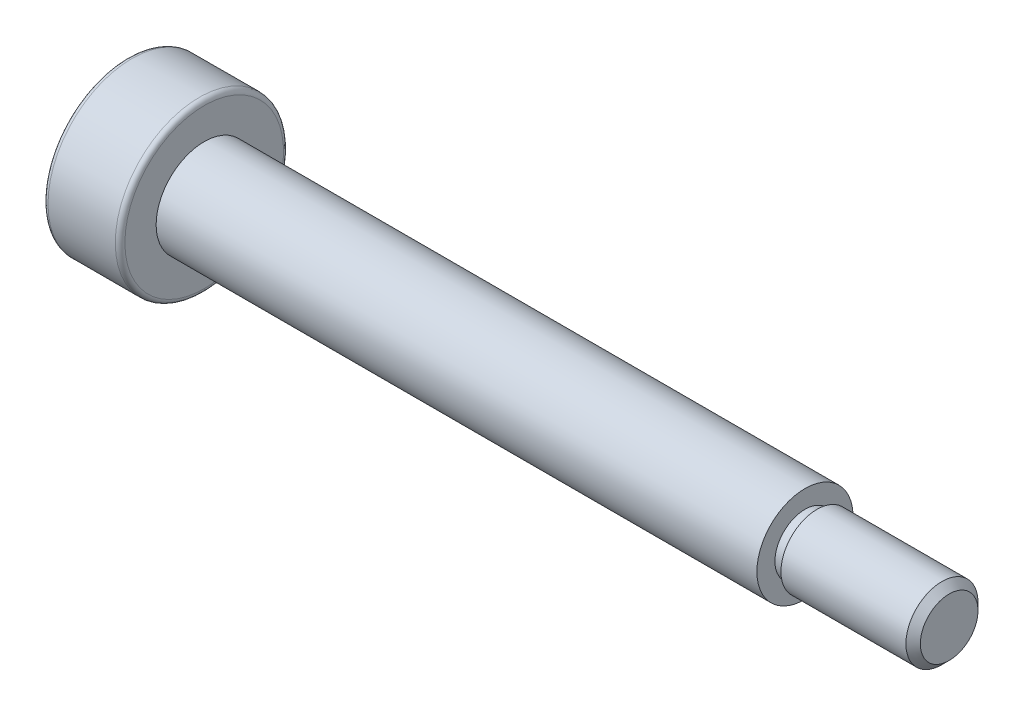
SolidWorks part; units mm, degrees
ref_plane "前视基准面" through (0, 0, 0) normal (0, 0, 1) x (1, 0, 0)
ref_plane "上视基准面" through (0, 0, 0) normal (0, 1, 0) x (1, 0, 0)
ref_plane "右视基准面" through (0, 0, 0) normal (1, 0, 0) x (0, 0, -1)
sketch "草图1" plane through (0, 0, 0) normal (0, 0, 1) x (1, 0, 0)
  line L0 (-17.1, 0) -> (17.1, 0) construction
  line L1 (-17.1, 0) -> (-17.1, 3.5)
  line L2 (-17.1, 3.5) -> (-13.9, 3.5)
  line L3 (-13.9, 3.5) -> (-13.9, 2)
  line L4 (-13.9, 2) -> (11.1, 2)
  line L5 (11.1, 2) -> (11.1, 1.5)
  line L6 (11.1, 1.5) -> (17.1, 1.5)
  line L7 (17.1, 1.5) -> (17.1, 0)
  line L8 (-17.1, 0) -> (17.1, 0)
  dimension "D1" = 4
  dimension "D2" = 7
  dimension "D3" = 3
  dimension "D4" = 6
  dimension "D5" = 25
  dimension "D6" = 3.2
revolve "旋转1" add sketch "草图1" angle 360 about L0
fillet "圆角1" radius 0.2 2 edges at (-13.9, 0, 3.5) (-17.1, 0, 3.5)
chamfer "倒角1" distance 0.3 angle 45 1 edges at (17.1, 0, 1.5)
sketch "草图3" plane through (0, 0, 0) normal (0, 0, 1) x (1, 0, 0)
  line L0 (11.1, 0) -> (16.8, 0) construction
  line L1 (11.1, -1.5) -> (11.1, 1.5) construction
  line L2 (16.8, 1.5) -> (16.8, -1.5) construction
  line L3 (11.1, -2) -> (11.1, 2) construction
  line L4 (11.1, 1.5) -> (11.6, 1.5)
  line L5 (11.1, 1.5) -> (11.1, 1.25)
  line L6 (11.1, 1.25) -> (11.6, 1.25)
  line L7 (11.6, 1.5) -> (11.6, 1.25)
  line L8 (16.8, 1.5) -> (11.1, 1.5) construction
  dimension "D1" = 2.5
  dimension "D2" = 0.5
revolve "切除-旋转1" cut sketch "草图3" angle 360 about L0
sketch "草图4" plane through (-17.1, 0, 0) normal (-1, 0, 0) x (0, 0, 1)
  line L1 (1.7321, 0) -> (0.866, 1.5)
  line L2 (0.866, 1.5) -> (-0.866, 1.5)
  line L3 (-0.866, 1.5) -> (-1.7321, 0)
  line L4 (-1.7321, 0) -> (-0.866, -1.5)
  line L5 (-0.866, -1.5) -> (0.866, -1.5)
  line L6 (0.866, -1.5) -> (1.7321, 0)
  circle A0 centre (0, 0) radius 1.5 construction
  dimension "D1" = 3
extrude "切除-拉伸1" cut sketch "草图4" against normal blind 2
